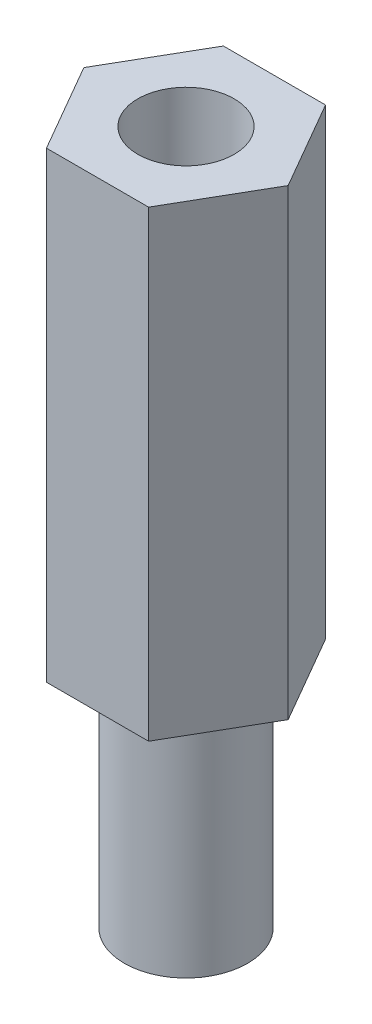
SolidWorks part; units mm, degrees
ref_plane "前视基准面" through (0, 0, 0) normal (0, 0, 1) x (1, 0, 0)
ref_plane "上视基准面" through (0, 0, 0) normal (0, 1, 0) x (1, 0, 0)
ref_plane "右视基准面" through (0, 0, 0) normal (1, 0, 0) x (0, 0, -1)
sketch "草图4" plane through (0, 0, 0) normal (0, 1, 0) x (1, 0, 0)
  line L0 (-12.7945, 0) -> (16.3015, 0) construction
  line L2 (1.325, -2.295) -> (2.65, 0)
  line L3 (2.65, 0) -> (1.325, 2.295)
  line L4 (1.325, 2.295) -> (-1.325, 2.295)
  line L5 (-1.325, 2.295) -> (-2.65, 0)
  line L6 (-2.65, 0) -> (-1.325, -2.295)
  line L7 (-1.325, -2.295) -> (1.325, -2.295)
  circle A0 centre (0, 0) radius 2.295 construction
  dimension "D1" = 5.3
extrude "凸台-拉伸1" add sketch "草图4" along normal blind 12
sketch "草图6" plane through (0, 0, 0) normal (0, -1, 0) x (-1, 0, 0)
  circle A0 centre (0, 0) radius 1.6
  dimension "D1" = 3.2
extrude "凸台-拉伸2" add sketch "草图6" along normal blind 6
cosmetic thread "装饰螺纹线1" parameters "D2"=2.5
sketch "草图7" plane through (0, 12, 0) normal (0, 1, 0) x (1, 0, 0)
  circle A0 centre (0, 0) radius 1.25
  dimension "D1" = 2.5
extrude "切除-拉伸1" cut sketch "草图7" against normal blind 5
cosmetic thread "装饰螺纹线2" parameters "D2"=3
